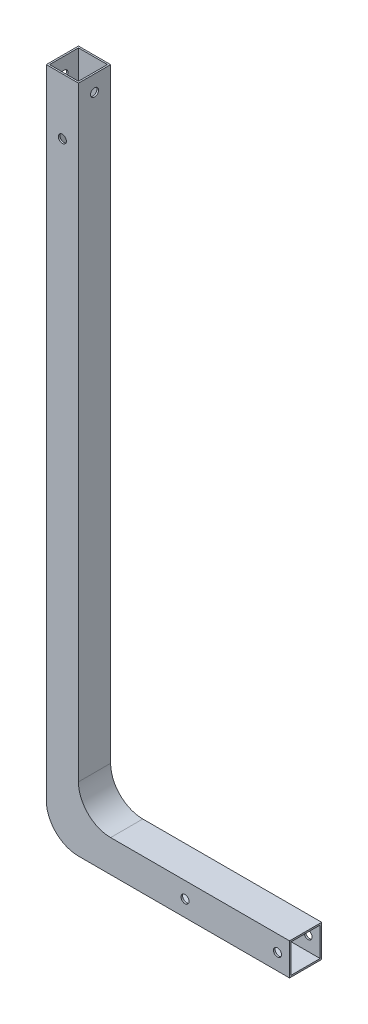
SolidWorks part; units mm, degrees
material "Alloy Steel"
ref_plane "Front Plane" through (0, 0, 0) normal (0, 0, 1) x (1, 0, 0)
ref_plane "Top Plane" through (0, 0, 0) normal (0, 1, 0) x (1, 0, 0)
ref_plane "Right Plane" through (0, 0, 0) normal (1, 0, 0) x (0, 0, -1)
sketch "Sketch1" plane through (0, 0, 0) normal (0, 0, 1) x (1, 0, 0)
  line L0 (0, 1057.275) -> (0, 50.8)
  line L1 (50.8, 0) -> (384.175, 0)
  line L2 (384.175, 0) -> (384.175, 50.8)
  line L3 (384.175, 50.8) -> (101.6, 50.8)
  line L4 (50.8, 101.6) -> (50.8, 1057.275)
  line L5 (50.8, 1057.275) -> (0, 1057.275)
  arc A0 (50.8, 101.6) -> (101.6, 50.8) centre (101.6, 101.6) ccw
  arc A1 (50.8, 0) -> (0, 50.8) centre (50.8, 50.8) cw
  point P11 (0, 0)
  dimension "D5" = 50.8
  dimension "D1" = 1057.275
  dimension "D2" = 384.175
  dimension "D3" = 50.8
  dimension "D4" = 50.8
extrude "Boss-Extrude1" add sketch "Sketch1" along normal blind 50.8
shell "Shell1" thickness 2.54
sketch "Sketch2" plane through (384.175, 0, 0) normal (1, 0, 0) x (0, 0, -1)
  line L0 (-2.54, 48.26) -> (-48.26, 48.26)
  line L5 (-48.26, 2.54) -> (-48.26, 48.26)
  line L6 (-2.54, 2.54) -> (-48.26, 2.54)
  line L7 (-2.54, 2.54) -> (-2.54, 48.26)
extrude "Cut-Extrude2" cut sketch "Sketch2" against normal blind 50.8
hole_wizard "#97 (0.5) Diameter Hole1" positions "3DSketch1" profile "Sketch3" hole size "#97" standard "ANSI Inch" end condition through all
sketch3d "3DSketch1"
  line L1 (384.175, 50.8, 50.8) -> (101.6, 50.8, 50.8) construction
  line L2 (384.175, 0, 50.8) -> (384.175, 50.8, 50.8) construction
  point P0 (365.125, 25.4, 50.8)
  point P2 (219.075, 25.4, 50.8)
  dimension "D1" = 25.4
  dimension "D2" = 25.4
  dimension "D3" = 19.05
  dimension "D4" = 146.05
sketch "Sketch3" plane through (365.125, 25.4, 50.8) normal (1, 0, 0) x (0, -1, 0)
  line L0 (0, 0) -> (0, 50.8)
  line L1 (0, 50.8) -> (6.35, 50.8)
  line L2 (6.35, 50.8) -> (6.35, 0)
  line L5 (6.35, 0) -> (0, 0)
  line L11 (0, -6.35) -> (0, 107.95) construction
  dimension "Thru Hole Dia." = 12.7
  dimension "Thru Hole Depth" = 50.8
hole_wizard "#97 (0.5) Diameter Hole2" positions "3DSketch2" profile "Sketch5" hole size "#97" standard "ANSI Inch" end condition through all
sketch3d "3DSketch2"
  line L0 (0, 1057.275, 50.8) -> (0, 1057.275, 0) construction
  line L1 (0, 1057.275, 0) -> (0, 50.8, 0) construction
  point P0 (0, 1031.875, 25.4)
  dimension "D1" = 25.4
  dimension "D2" = 25.4
sketch "Sketch5" plane through (0, 1031.875, 25.4) normal (0, 1, 0) x (0, 0, 1)
  line L0 (0, 0) -> (0, 384.175)
  line L1 (0, 384.175) -> (6.35, 384.175)
  line L2 (6.35, 384.175) -> (6.35, 0)
  line L5 (6.35, 0) -> (0, 0)
  line L11 (0, -6.35) -> (0, 107.95) construction
  dimension "Thru Hole Dia." = 12.7
  dimension "Thru Hole Depth" = 384.175
hole_wizard "#97 (0.5) Diameter Hole3" positions "3DSketch3" profile "Sketch6" hole size "#97" standard "ANSI Inch" end condition through all
sketch3d "3DSketch3"
  line L0 (50.8, 1057.275, 50.8) -> (0, 1057.275, 50.8) construction
  line L1 (0, 1057.275, 50.8) -> (0, 50.8, 50.8) construction
  point P0 (25.4, 968.375, 50.8)
  dimension "D1" = 88.9
  dimension "D2" = 25.4
sketch "Sketch6" plane through (25.4, 968.375, 50.8) normal (1, 0, 0) x (0, -1, 0)
  line L0 (0, 0) -> (0, 50.8)
  line L1 (0, 50.8) -> (6.35, 50.8)
  line L2 (6.35, 50.8) -> (6.35, 0)
  line L5 (6.35, 0) -> (0, 0)
  line L11 (0, -6.35) -> (0, 107.95) construction
  dimension "Thru Hole Dia." = 12.7
  dimension "Thru Hole Depth" = 50.8
